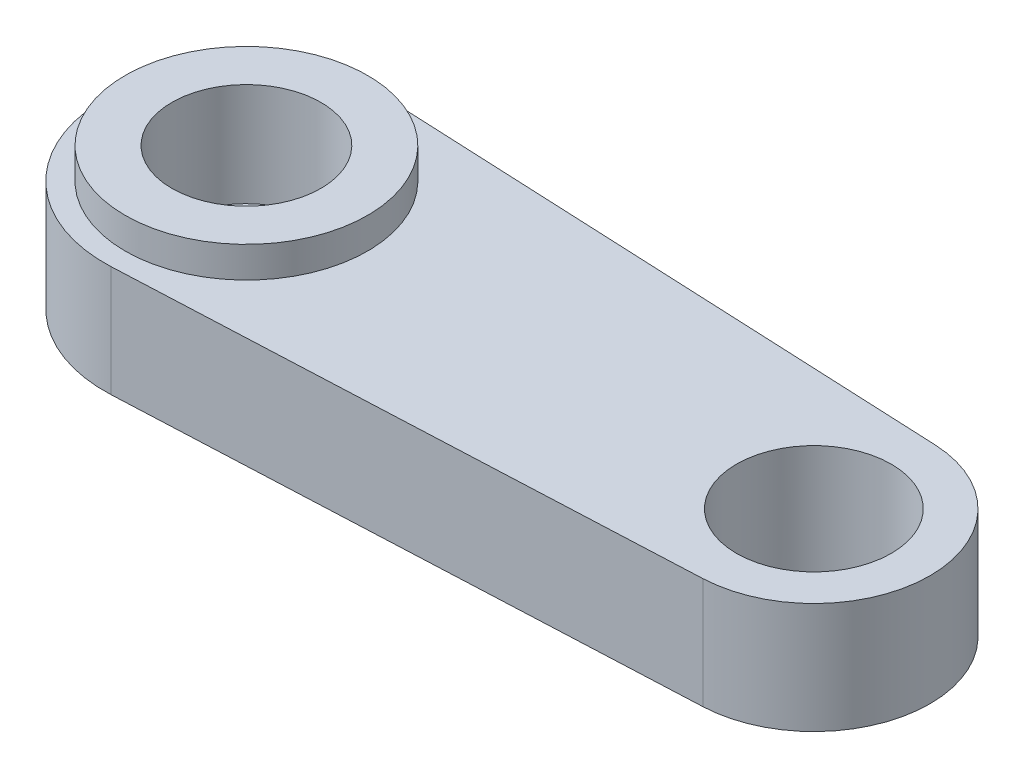
SolidWorks part; units mm, degrees
ref_plane "Front Plane" through (0, 0, 0) normal (0, 0, 1) x (1, 0, 0)
ref_plane "Top Plane" through (0, 0, 0) normal (0, 1, 0) x (1, 0, 0)
ref_plane "Right Plane" through (0, 0, 0) normal (1, 0, 0) x (0, 0, -1)
sketch "Sketch1" plane through (0, 0, 0) normal (0, 1, 0) x (1, 0, 0)
  line L0 (0.25, 5.4943) -> (22.2045, 4.4953)
  line L1 (22.2045, -4.4953) -> (0.25, -5.4943)
  circle A0 centre (0, 0) radius 1.5
  circle A1 centre (22, 0) radius 3
  arc A2 (0.25, 5.4943) -> (0.25, -5.4943) centre (0, 0) ccw
  arc A3 (22.2045, 4.4953) -> (22.2045, -4.4953) centre (22, 0) cw
  dimension "D2" = 6
  dimension "D3" = 3
  dimension "D4" = 4.5
  dimension "D5" = 5.5
  dimension "D1" = 22
extrude "Boss-Extrude1" add sketch "Sketch1" along normal blind 3.5 contours A0 | A1 | L1 A2 L0 A3
sketch "Sketch2" plane through (0, 3.5, 0) normal (0, 1, 0) x (1, 0, 0)
  circle A0 centre (0, 0) radius 2.89
  circle A3 centre (0, 0) radius 4.7
  dimension "D1" = 5.78
  dimension "D2" = 9.4
extrude "Boss-Extrude2" add sketch "Sketch2" along normal blind 3
sketch "Sketch3" plane through (0, 3.5, 0) normal (0, 1, 0) x (1, 0, 0)
  circle A0 centre (0, 0) radius 2.89 construction
  circle A1 centre (0, 0) radius 2.89
extrude "Cut-Extrude1" cut sketch "Sketch3" against normal blind 1
sketch "Sketch4" plane through (0, 3.5, 0) normal (0, 1, 0) x (1, 0, 0)
  line L2 (22.2045, 4.4953) -> (0.25, 5.4943)
  line L3 (0.25, -5.4943) -> (22.2045, -4.4953)
  line L4 (22.2045, 4.4953) -> (0.25, 5.4943)
  line L5 (0.25, -5.4943) -> (22.2045, -4.4953)
  circle A1 centre (0, 0) radius 1.5 construction
  arc A2 (22.2045, -4.4953) -> (22.2045, 4.4953) centre (22, 0) ccw
  arc A3 (0.25, 5.4943) -> (0.25, -5.4943) centre (0, 0) ccw
  arc A4 (22.2045, -4.4953) -> (22.2045, 4.4953) centre (22, 0) ccw
  arc A5 (0.25, 5.4943) -> (0.25, -5.4943) centre (0, 0) ccw
  circle A6 centre (0, 0) radius 1.5
  circle A7 centre (22, 0) radius 3 construction
  circle A8 centre (22, 0) radius 3
  circle A9 centre (0, 0) radius 2.89 construction
  circle A10 centre (0, 0) radius 2.89
  circle M8 centre (0, 0) radius 4.7
  arc M9 (22.2045, -4.4953) -> (22.2045, 4.4953) centre (22, 0) ccw
  line M10 (22.2045, 4.4953) -> (0.25, 5.4943)
  arc M11 (0.25, 5.4943) -> (0.25, -5.4943) centre (0, 0) ccw
  line M12 (0.25, -5.4943) -> (22.2045, -4.4953)
  circle M13 centre (22, 0) radius 3
  dimension "D1" = 0
extrude "Boss-Extrude3" add sketch "Sketch4" along normal blind 1.8 contours M12 M9 M10 M11 M13 M8
sketch "Sketch5" plane through (0, 0, 0) normal (0, -1, 0) x (1, 0, 0)
  line L2 (22.2045, 4.4953) -> (0.25, 5.4943)
  line L3 (0.25, -5.4943) -> (22.2045, -4.4953)
  line L4 (22.2045, 4.4953) -> (0.25, 5.4943)
  line L5 (0.25, -5.4943) -> (22.2045, -4.4953)
  arc A2 (22.2045, -4.4953) -> (22.2045, 4.4953) centre (22, 0) ccw
  arc A3 (0.25, 5.4943) -> (0.25, -5.4943) centre (0, 0) ccw
  arc A4 (22.2045, -4.4953) -> (22.2045, 4.4953) centre (22, 0) ccw
  arc A5 (0.25, 5.4943) -> (0.25, -5.4943) centre (0, 0) ccw
  dimension "D1" = 0
extrude "Cut-Extrude2" cut sketch "Sketch5" against normal blind 1
